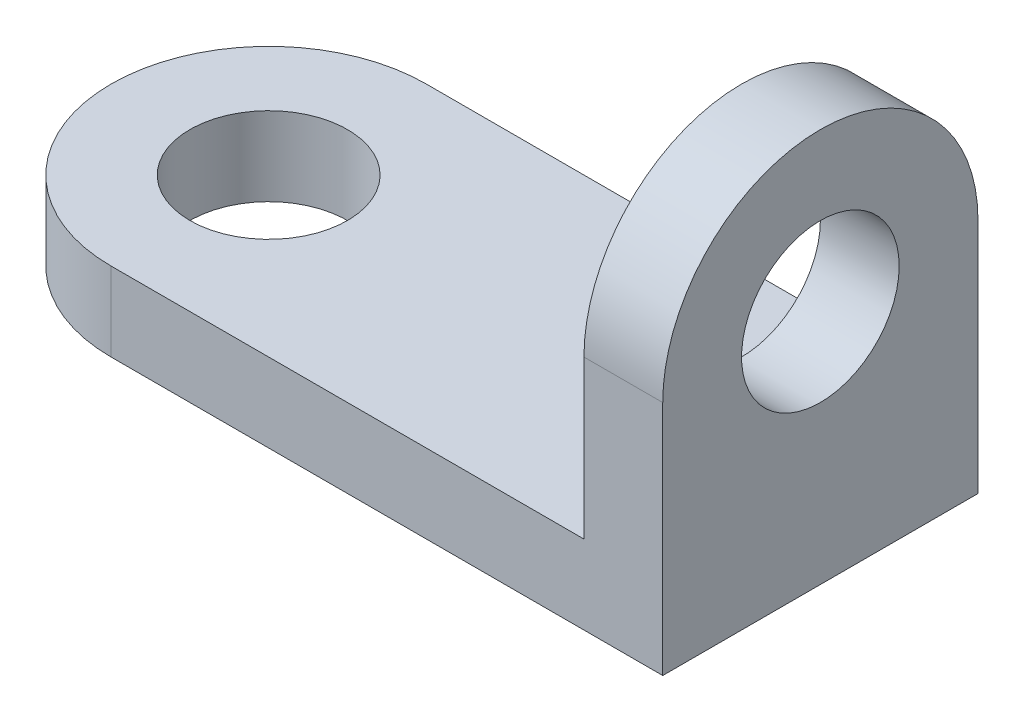
SolidWorks part; units mm, degrees
ref_plane "Front Plane" through (0, 0, 0) normal (0, 0, 1) x (1, 0, 0)
ref_plane "Top Plane" through (0, 0, 0) normal (0, 1, 0) x (1, 0, 0)
ref_plane "Right Plane" through (0, 0, 0) normal (1, 0, 0) x (0, 0, -1)
sketch "Sketch1" plane through (0, 0, 0) normal (0, 1, 0) x (1, 0, 0)
  line L1 (-35, 20) -> (35, 20)
  line L2 (-35, 20) -> (-35, -20) construction
  line L3 (-35, -20) -> (35, -20)
  line L4 (35, 20) -> (35, -20)
  line L5 (-35, 20) -> (35, -20) construction
  line L6 (-35, -20) -> (35, 20) construction
  arc A0 (-35, 20) -> (-35, -20) centre (-35, 0) ccw
  circle A1 centre (-35, 0) radius 10
  point P0 (0, 0)
  dimension "D3" = 20
  dimension "D1" = 40
  dimension "D2" = 70
extrude "Boss-Extrude1" add sketch "Sketch1" along normal blind 10
sketch "Sketch3" plane through (35, 0, 0) normal (1, 0, 0) x (0, 0, -1)
  line L0 (-20, 10) -> (20, 10)
  line L1 (-20, 10) -> (-20, 30)
  line L2 (20, 10) -> (20, 30)
  line L3 (-20, 30) -> (20, 30) construction
  arc A0 (-20, 30) -> (20, 30) centre (0, 30) cw
  circle A1 centre (0, 30) radius 10
  dimension "D2" = 20
  dimension "D1" = 20
extrude "Boss-Extrude2" add sketch "Sketch3" against normal blind 10
